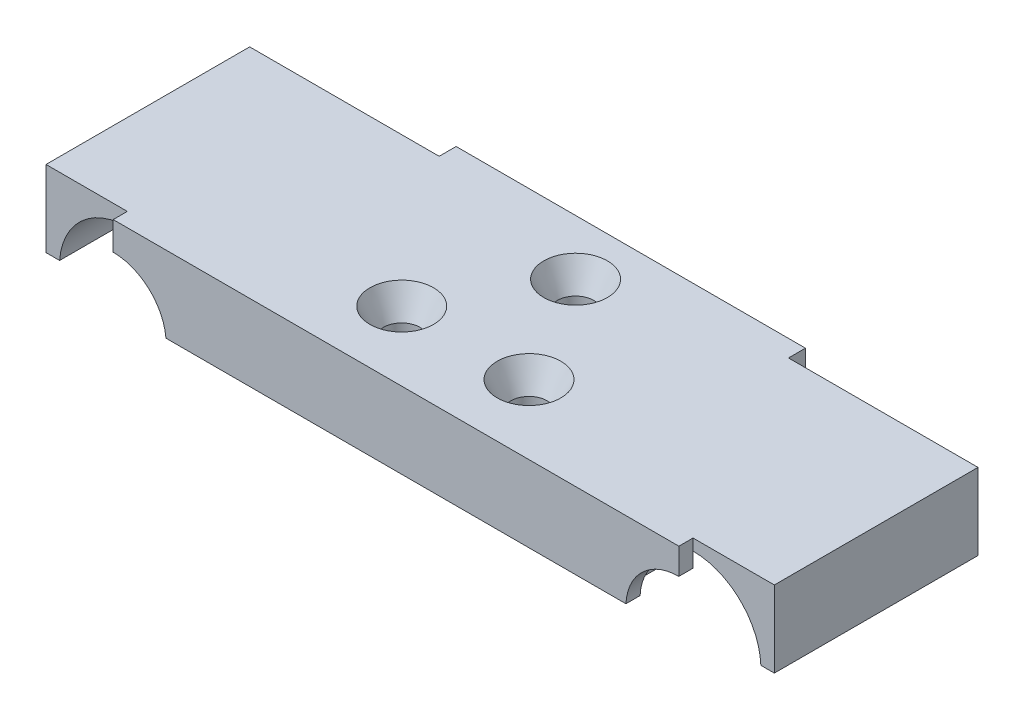
SolidWorks part; units mm, degrees
material "ABS"
ref_plane "Front Plane" through (0, 0, 0) normal (0, 0, 1) x (1, 0, 0)
ref_plane "Top Plane" through (0, 0, 0) normal (0, 1, 0) x (1, 0, 0)
ref_plane "Right Plane" through (0, 0, 0) normal (1, 0, 0) x (0, 0, -1)
sketch "Sketch1" plane through (0, 0, 0) normal (0, 1, 0) x (1, 0, 0)
  line L0 (32.7025, 0) -> (-32.7025, 0)
  line L1 (-32.7025, 0) -> (-32.7025, 18.288)
  line L2 (-32.7025, 18.288) -> (-15.6845, 18.288)
  line L3 (-15.6845, 18.288) -> (-15.6845, 19.812)
  line L4 (-15.6845, 19.812) -> (15.6845, 19.812)
  line L5 (15.6845, 19.812) -> (15.6845, 18.288)
  line L6 (15.6845, 18.288) -> (32.7025, 18.288)
  line L7 (32.7025, 18.288) -> (32.7025, 0)
  point P4 (0, 0)
  dimension "D1" = 31.369
  dimension "D2" = 65.405
  dimension "D3" = 18.288
  dimension "D4" = 19.812
  dimension "D5" = 18.288
extrude "Boss-Extrude1" add sketch "Sketch1" along normal blind 7.112
sketch "Sketch2" plane through (0, 0, 0) normal (0, 0, 1) x (1, 0, 0)
  line L0 (-32.7025, 0) -> (32.7025, 0) construction
  line L1 (-32.7025, 7.112) -> (-32.7025, 0) construction
  line L2 (-32.7025, 7.112) -> (32.7025, 7.112) construction
  circle A0 centre (-25.4, -0.1905) radius 4.7625
  circle A1 centre (25.3996, 0) radius 4.7625
  dimension "D1" = 9.525
  dimension "D2" = 50.8
  dimension "D3" = 7.3025
  dimension "D4" = 7.3025
extrude "Cut-Extrude1" cut sketch "Sketch2" against normal through all
sketch "Sketch3" plane through (0, 0, 0) normal (0, 0, 1) x (1, 0, 0)
  circle A0 centre (-25.4, -0.1905) radius 6.096
  circle A1 centre (25.3996, 0) radius 6.096
  dimension "D1" = 12.192
extrude "Cut-Extrude2" cut sketch "Sketch3" against normal blind 10.668
sketch "Sketch5" plane through (0, 7.112, 0) normal (0, 1, 0) x (1, 0, 0)
  line L0 (0, 4.9567) -> (0, 0) construction
  line L2 (0, 14.8553) -> (0, 19.812) construction
  line L3 (15.6845, 19.812) -> (-15.6845, 19.812) construction
  line L5 (0, 14.8553) -> (-5.715, 4.9567)
  line L6 (-5.715, 4.9567) -> (5.715, 4.9567)
  line L7 (5.715, 4.9567) -> (0, 14.8553)
  circle A0 centre (0, 8.2562) radius 3.2996 construction
  dimension "D1" = 11.43
hole_wizard "CSK for #4 Flat Head Machine Screw (100)1" positions "Sketch10" profile "Sketch9" countersink size "#4" standard "ANSI Inch" end condition through all
sketch "Sketch10" plane through (0, 7.112, 0) normal (0, 1, 0) x (1, 0, 0)
  point P0 (0, 14.8553)
  point P3 (-5.715, 4.9567)
  point P6 (5.715, 4.9567)
sketch "Sketch9" plane through (0, 7.112, -14.8553) normal (1, 0, 0) x (0, 0, 1)
  line L0 (0, 0) -> (0, 7.112)
  line L1 (0, 7.112) -> (1.6319, 7.112)
  line L2 (1.6319, 7.112) -> (1.6319, 2.4638)
  line L3 (1.6319, 2.4638) -> (2.8575, 0)
  line L5 (2.8575, 0) -> (0, 0)
  line L6 (-1.632, 2.4638) -> (-2.8575, 0) construction
  line L11 (0, -6.35) -> (0, 107.95) construction
  dimension "Thru Hole Dia." = 3.2639
  dimension "Thru Hole Depth" = 7.112
  dimension "Near C'Sink Dia." = 5.715
sketch "Sketch11" plane through (0, 0, 0) normal (0, 0, 1) x (1, 0, 0)
  line L2 (-19.307, 0) -> (-20.6413, 0) construction
  line L3 (-20.6413, 0) -> (20.6371, 0)
  line L8 (25.3996, 7.112) -> (-25.4, 7.112)
  line L11 (25.3996, 4.7625) -> (25.3996, 7.112)
  line L12 (-25.4, 4.572) -> (-25.4, 7.112)
  arc A0 (-25.4, 4.572) -> (-20.6413, 0) centre (-25.4, -0.1905) cw
  arc A1 (20.6371, 0) -> (25.3996, 4.7625) centre (25.3996, 0) cw
  dimension "D1" = 4.7625
  dimension "D2" = 7.112
extrude "Boss-Extrude2" add sketch "Sketch11" along normal blind 1.27
sketch "Sketch12" plane through (0, 0, -19.812) normal (0, 0, -1) x (-1, 0, 0)
  line L0 (32.7025, 7.112) -> (32.7025, 0) construction
  line L1 (-32.7025, 0) -> (32.7025, 0)
  line L2 (-32.7025, 0) -> (-32.7025, 0.254)
  line L3 (-32.7025, 0.254) -> (32.7025, 0.254)
  line L4 (32.7025, 0) -> (32.7025, 0.254)
  dimension "D1" = 0.254
extrude "Cut-Extrude3" cut sketch "Sketch12" against normal through all
